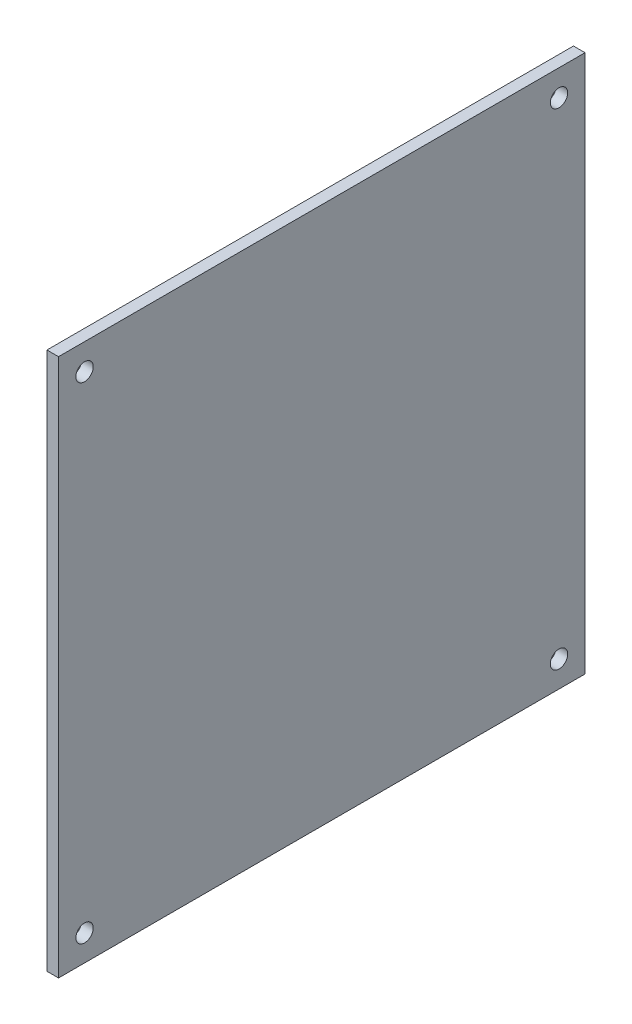
SolidWorks part; units mm, degrees
ref_plane "Спереди" through (0, 0, 0) normal (0, 0, 1) x (1, 0, 0)
ref_plane "Сверху" through (0, 0, 0) normal (0, 1, 0) x (1, 0, 0)
ref_plane "Справа" through (0, 0, 0) normal (1, 0, 0) x (0, 0, -1)
sketch "Эскиз1" plane through (0, 0, 0) normal (1, 0, 0) x (0, 0, -1)
  line L1 (-30.8705, 49.6979) -> (60.1295, 49.6979)
  line L2 (-30.8705, 49.6979) -> (-30.8705, -43.3021)
  line L3 (-30.8705, -43.3021) -> (60.1295, -43.3021)
  line L4 (60.1295, 49.6979) -> (60.1295, -43.3021)
  circle A0 centre (-26.3705, 45.1979) radius 1.5
  circle A1 centre (55.6295, 45.1979) radius 1.5
  circle A2 centre (55.6295, -38.8021) radius 1.5
  circle A3 centre (-26.3705, -38.8021) radius 1.5
extrude "Бобышка-Вытянуть1" add sketch "Эскиз1" along normal blind 2
